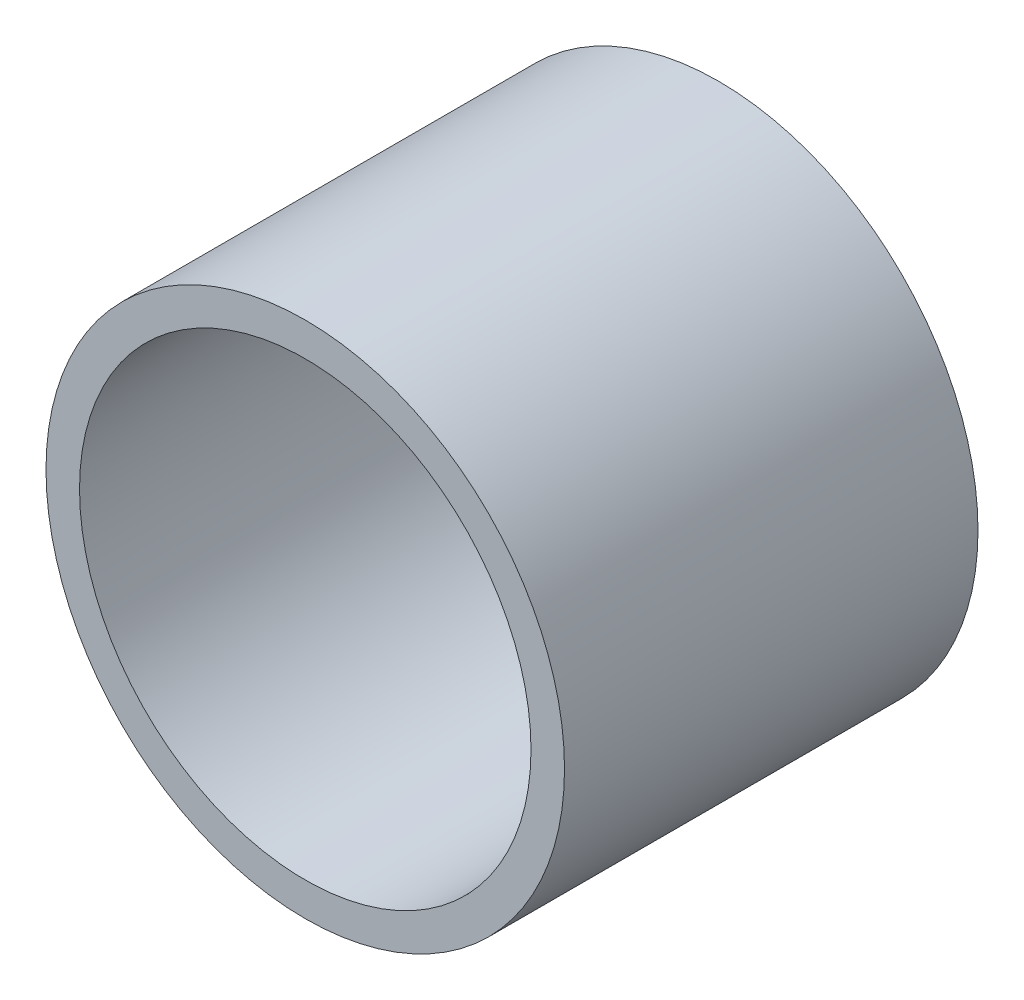
SolidWorks part; units mm, degrees
ref_plane "Alzado" through (0, 0, 0) normal (0, 0, 1) x (1, 0, 0)
ref_plane "Planta" through (0, 0, 0) normal (0, 1, 0) x (1, 0, 0)
ref_plane "Vista lateral" through (0, 0, 0) normal (1, 0, 0) x (0, 0, -1)
sketch "Croquis1" plane through (0, 0, 0) normal (0, 0, 1) x (1, 0, 0)
  circle A0 centre (0, 0) radius 10.1
  circle A1 centre (0, 0) radius 11.6
extrude "Saliente-Extruir1" add sketch "Croquis1" along normal blind 16
sketch "Croquis2" plane through (0, 0, 0) normal (0, 0, -1) x (-1, 0, 0)
  circle A0 centre (0, 0) radius 11.6
extrude "Saliente-Extruir2" add sketch "Croquis2" along normal blind 2.5
sketch "Croquis3" plane through (0, 0, -2.5) normal (0, 0, -1) x (-1, 0, 0)
  circle A0 centre (0, 0) radius 3.15
extrude "Cortar-Extruir1" cut sketch "Croquis3" against normal blind 2
